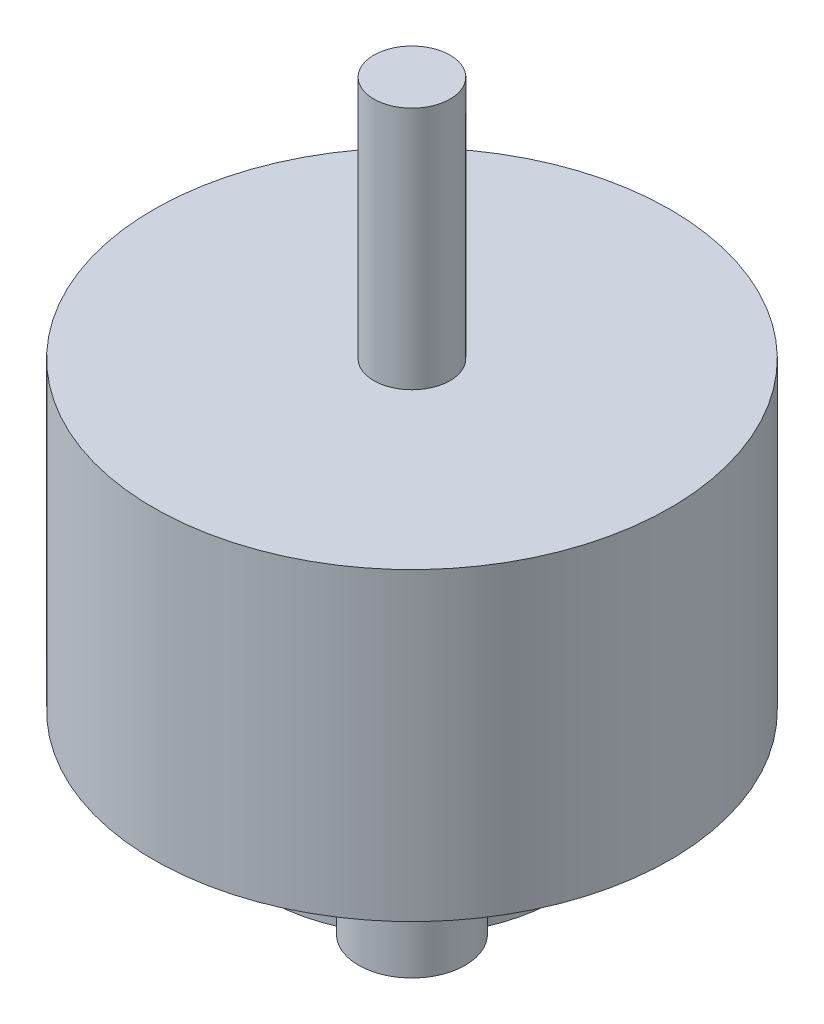
SolidWorks part; units mm, degrees
ref_plane "Plan de face" through (0, 0, 0) normal (0, 0, 1) x (1, 0, 0)
ref_plane "Plan de dessus" through (0, 0, 0) normal (0, 1, 0) x (1, 0, 0)
ref_plane "Plan de droite" through (0, 0, 0) normal (1, 0, 0) x (0, 0, -1)
sketch "Esquisse1" plane through (0, 0, 0) normal (0, 0, 1) x (1, 0, 0)
  line L0 (0, 0) -> (0, 42) construction
  line L1 (0, 0) -> (-9.5, 0)
  line L2 (-9.5, 0) -> (-9.5, 3.5)
  line L3 (-9.5, 3.5) -> (-7.5, 3.5)
  line L4 (-7.5, 3.5) -> (-6.95, 6)
  line L5 (-6.95, 6) -> (-16.95, 6)
  line L6 (-16.95, 6) -> (-16.95, 26)
  line L7 (-16.95, 26) -> (-2.5, 26)
  line L8 (-2.5, 26) -> (-2.5, 42)
  line L9 (-2.5, 42) -> (0, 42)
  line L10 (0, 0) -> (0, 42)
  point P2 (-1.25, 42)
  dimension "D1" = 42
  dimension "D2" = 33.9
  dimension "D3" = 5
  dimension "D4" = 19
  dimension "D5" = 2
  dimension "D6" = 16
  dimension "D7" = 3.5
  dimension "D8" = 2.5
  dimension "D9" = 10
revolve "Révolution1" add sketch "Esquisse1" angle 360 about L0
sketch "Esquisse2" plane through (0, 0, 0) normal (0, -1, 0) x (-1, 0, 0)
  line L0 (0, 0) -> (0, -9.5) construction
  line L1 (6.7175, -6.7175) -> (0, 0) construction
  line L2 (0, 0) -> (6.7175, -6.7175) construction
  line L3 (0, 0) -> (-6.7175, -6.7175) construction
  circle A0 centre (6.7175, -6.7175) radius 3.5
  circle A1 centre (0, 0) radius 9.5 construction
  circle A2 centre (-6.7175, -6.7175) radius 3.5
  circle A3 centre (-6.7175, 6.7175) radius 3.5
  circle A4 centre (6.7175, 6.7175) radius 3.5
  dimension "D1" = 7
  dimension "D2" = 45
  dimension "D4" = 90
  dimension "D5" = 9.5
  dimension "D3" = 4
extrude "Boss.-Extru.1" add sketch "Esquisse2" against normal up to surface (3.5 mm away) up to face at (0, 3.5, -9.5)
hole_wizard "Dégagement M31" positions "Esquisse3D1" profile "Esquisse3" hole size "M3" standard "ISO"
sketch3d "Esquisse3D1"
  line L0 (0, 0, 0) -> (0, 0, 9.5) construction
  line L2 (-6.7175, 0, 6.7175) -> (0, 0, 0) construction
  line L4 (6.7175, 0, 6.7175) -> (0, 0, 0) construction
  line L6 (6.7175, 0, -6.7175) -> (0, 0, 0) construction
  line L8 (0, 0, 0) -> (-6.7175, 0, -6.7175) construction
  circle A2 centre (0, 0, 0) radius 9.5
  point P0 (-6.7175, 0, 6.7175)
  point P2 (6.7175, 0, 6.7175)
  point P4 (6.7175, 0, -6.7175)
  point P6 (-6.7175, 0, -6.7175)
  point P17 (0, 9.5, 0)
  dimension "D1" = 19
  dimension "D2" = 45
  dimension "D3" = 45
  dimension "D4" = 90
  dimension "D5" = 90
sketch "Esquisse3" plane through (-6.7175, 0, 6.7175) normal (1, 0, 0) x (0, 0, -1)
  line L0 (0, 0) -> (0, 3.5)
  line L1 (0, 3.5) -> (1.7, 3.5)
  line L2 (1.7, 3.5) -> (1.7, 0)
  line L5 (1.7, 0) -> (0, 0)
  line L11 (0, -6.35) -> (0, 107.95) construction
  dimension "Diamètre du perçage jusqu'au prochain" = 3.4
  dimension "Profondeur du perçage jusqu'au prochain" = 3.5
